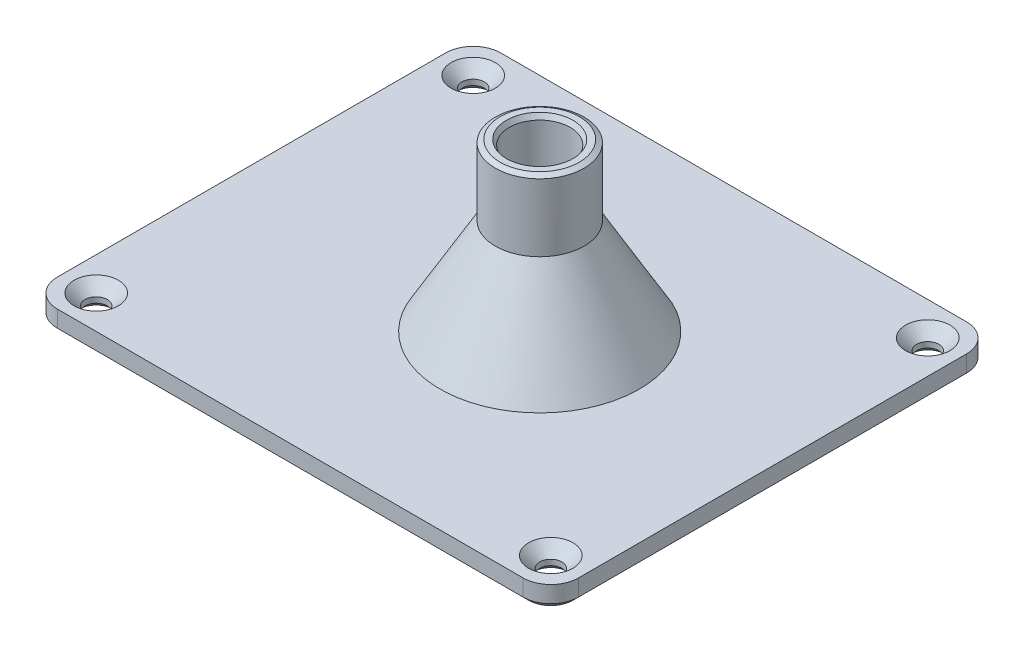
SolidWorks part; units mm, degrees
ref_plane "Спереди" through (0, 0, 0) normal (0, 0, 1) x (1, 0, 0)
ref_plane "Сверху" through (0, 0, 0) normal (0, 1, 0) x (1, 0, 0)
ref_plane "Справа" through (0, 0, 0) normal (1, 0, 0) x (0, 0, -1)
sketch "Эскиз1" plane through (0, 0, 0) normal (0, 1, 0) x (1, 0, 0)
  line L1 (-47, -40) -> (47, -40)
  line L2 (-47, -40) -> (-47, 40)
  line L3 (-47, 40) -> (47, 40)
  line L4 (47, -40) -> (47, 40)
  line L5 (0, 40) -> (0, -40) construction
  line L6 (-47, 0) -> (47, 0) construction
  circle A0 centre (41, 34) radius 2
  circle A1 centre (-41, 34) radius 2
  circle A2 centre (-41, -34) radius 2
  circle A3 centre (41, -34) radius 2
  point P0 (0, 0)
  dimension "D3" = 82
  dimension "D4" = 68
  dimension "D5" = 4
  dimension "D1" = 94
  dimension "D2" = 80
extrude "Бобышка-Вытянуть1" add sketch "Эскиз1" along normal blind 4
fillet "Скругление1" radius 5 4 edges at (-47, 2, 40) (-47, 2, -40) (47, 2, -40) (47, 2, 40)
sketch "Эскиз2" plane through (0, 4, 0) normal (0, 1, 0) x (1, 0, 0)
  line L0 (-11.4141, 0) -> (66.9074, 0) construction
  circle A0 centre (5, 0) radius 8
  circle A1 centre (41, 34) radius 2 construction
  dimension "D1" = 16
  dimension "D2" = 34
  dimension "D3" = 36
extrude "Бобышка-Вытянуть2" add sketch "Эскиз2" along normal blind 30
sketch "Эскиз3" plane through (0, 34, 0) normal (0, 1, 0) x (1, 0, 0)
  circle A0 centre (5, 0) radius 5.5
  dimension "D1" = 11
extrude "Вырез-Вытянуть1" cut sketch "Эскиз3" against normal through all
chamfer "Фаска1" distance 1 angle 45 13 edges at (41, 0, 32) (-41, 0, -36) (45.5355, 0, 38.5355) (47, 0, 0) (45.5355, 0, -38.5355) (0, 0, -40) (-45.5355, 0, -38.5355) (-47, 0, 0) (-45.5355, 0, 38.5355) (0, 0, 40) (41, 0, -32) (-41, 0, 36) (5, 0, 5.5)
chamfer "Фаска2" distance 10 angle 60 1 edges at (5, 4, 8)
chamfer "Фаска3" distance 2 angle 45 4 edges at (-41, 4, 36) (41, 4, 32) (41, 4, -32) (-41, 4, -36)
chamfer "Фаска4" distance 0.5 angle 60 2 edges at (5, 34, 5.5) (5, 34, 8)
